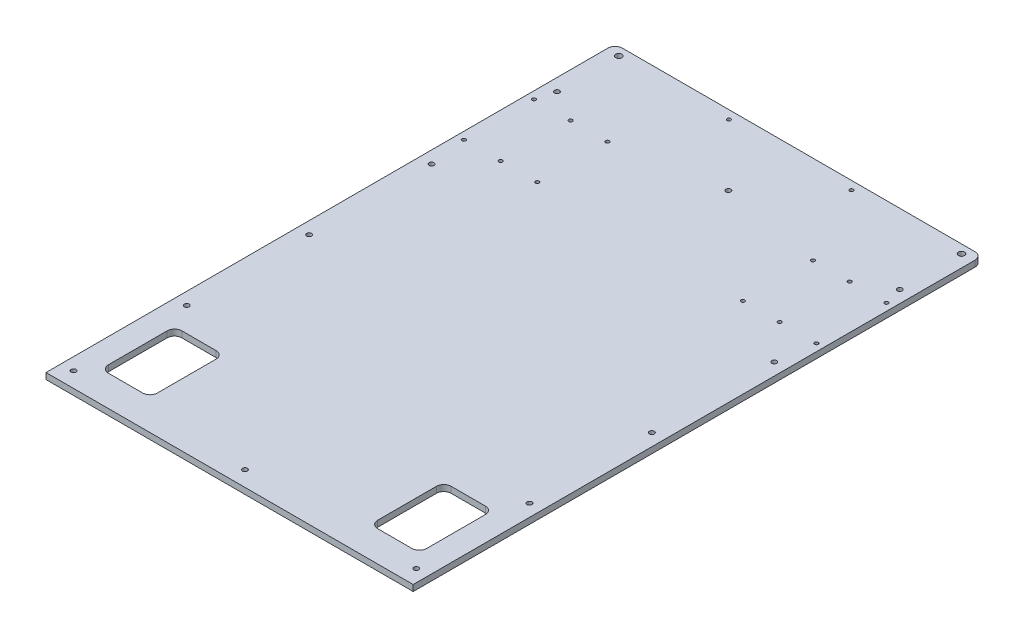
SolidWorks part; units mm, degrees
ref_plane "Front Plane" through (0, 0, 0) normal (0, 0, 1) x (1, 0, 0)
ref_plane "Top Plane" through (0, 0, 0) normal (0, 1, 0) x (1, 0, 0)
ref_plane "Right Plane" through (0, 0, 0) normal (1, 0, 0) x (0, 0, -1)
sketch "Sketch1" plane through (0, 0, 0) normal (0, 1, 0) x (1, 0, 0)
  line L0 (0, -210) -> (0, 210) construction
  line L1 (-150, -210) -> (150, -210)
  line L2 (-150, -210) -> (-150, 210)
  line L3 (-150, 210) -> (150, 210) construction
  line L4 (150, -210) -> (150, 210)
  line L5 (-150, 0) -> (150, 0) construction
  line L6 (-250, 154.9706) -> (0, 404.9706) construction
  line L7 (0, 404.9706) -> (250, 154.9706) construction
  line L8 (-130, -185) -> (-90, -185)
  line L9 (-130, -185) -> (-130, -125)
  line L10 (-130, -125) -> (-90, -125)
  line L11 (-90, -185) -> (-90, -125)
  line L12 (-130, -185) -> (-90, -125) construction
  line L13 (-130, -125) -> (-90, -185) construction
  line L14 (-250, 260) -> (250, 260) construction
  line L15 (-250, 260) -> (-250, -240) construction
  line L16 (-250, -240) -> (250, -240) construction
  line L17 (250, 260) -> (250, -240) construction
  line L18 (-188, 200) -> (-140, 200) construction
  line L19 (-165, 186) -> (-155, 186) construction
  line L20 (-165, 186) -> (-165, 122) construction
  line L21 (-165, 122) -> (-155, 122) construction
  line L22 (-155, 186) -> (-155, 122) construction
  line L23 (-140, 200) -> (-140, 248) construction
  line L24 (-140, 210) -> (-140, -210) construction
  line L25 (-150, -197.5) -> (150, -197.5) construction
  line L26 (-130, -155) -> (-90, -155) construction
  line L27 (-110, -185) -> (-110, -125) construction
  line L28 (-140, 248) -> (150, 248) construction
  line L30 (0, 182.625) -> (-150, 182.625) construction
  line L31 (130, -185) -> (90, -185)
  line L32 (130, -185) -> (130, -125)
  line L33 (130, -125) -> (90, -125)
  line L34 (90, -185) -> (90, -125)
  line L35 (-200, -205) -> (-200, 200) construction
  line L36 (-155, 154) -> (0, 154) construction
  line L37 (-150, 190) -> (0, 190) construction
  line L38 (-150, 118) -> (0, 118) construction
  line L39 (-150, 210) -> (-150, 255)
  line L40 (-150, 255) -> (150, 255)
  line L41 (150, 255) -> (150, 210)
  circle A0 centre (-140, 248) radius 12 construction
  circle A1 centre (-188, 200) radius 12 construction
  circle A2 centre (-188, -205) radius 12 construction
  circle A3 centre (0, -197.5) radius 2
  circle A4 centre (-140, -197.5) radius 2
  circle A9 centre (-140, 197.5) radius 2
  circle A10 centre (0, 197.5) radius 2
  circle A15 centre (-140, -5) radius 2
  circle A16 centre (-140, 95) radius 2
  circle A18 centre (0, 197.5) radius 2
  circle A20 centre (140, 197.5) radius 2
  circle A30 centre (140, -197.5) radius 2
  circle A31 centre (-114, 182.625) radius 1.5
  circle A32 centre (-144, 182.625) radius 1.5
  circle A33 centre (-84, 182.625) radius 1.5
  circle A34 centre (-84, 125.375) radius 1.5
  circle A35 centre (-114, 125.375) radius 1.5
  circle A36 centre (-144, 125.375) radius 1.5
  circle A37 centre (-140, -105) radius 2
  circle A38 centre (-140, 248) radius 2.5
  circle A39 centre (-50, 248) radius 1.5
  circle A40 centre (140, -105) radius 2
  circle A41 centre (140, -197.5) radius 2
  circle A42 centre (140, 95) radius 2
  circle A43 centre (140, -5) radius 2
  circle A44 centre (144, 125.375) radius 1.5
  circle A45 centre (114, 125.375) radius 1.5
  circle A46 centre (84, 125.375) radius 1.5
  circle A47 centre (84, 182.625) radius 1.5
  circle A48 centre (144, 182.625) radius 1.5
  circle A49 centre (114, 182.625) radius 1.5
  circle A50 centre (140, 197.5) radius 2
  circle A51 centre (50, 248) radius 1.5
  circle A52 centre (140, 248) radius 2.5
  point P0 (0, 0)
  point P8 (-110, -155)
  point P17 (0, -240)
  point P118 (150, 248)
  dimension "D15" = 24
  dimension "D16" = 10
  dimension "D22" = 80
  dimension "D23" = 5
  dimension "D24" = 3
  dimension "D25" = 4
  dimension "D27" = 36
  dimension "D28" = 30
  dimension "D29" = 200
  dimension "D30" = 90
  dimension "D33" = 100
  dimension "D34" = 30
  dimension "D35" = 36
  dimension "D37" = 3
  dimension "D38" = 57.25
  dimension "D20" = 4
  dimension "D21" = 100
  dimension "D1" = 300
  dimension "D2" = 420
  dimension "D3" = 60
  dimension "D4" = 40
  dimension "D5" = 20
  dimension "D6" = 25
  dimension "D7" = 500
  dimension "D8" = 500
  dimension "D9" = 45
  dimension "D10" = 45
  dimension "D11" = 50
  dimension "D12" = 64
  dimension "D13" = 10
  dimension "D14" = 5
  dimension "D17" = 5
  dimension "D18" = 10
  dimension "D19" = 12.5
  dimension "D26" = 20
  dimension "D36" = 36
  dimension "D39" = 45
  dimension "D40" = 23
extrude "Boss-Extrude1" add sketch "Sketch1" along normal blind 5 contours L41 L40 L39 L2 L1 L4 A51 A48 A43 A40 A39 A38 A37 A35 A30 A20 A16 A15 A9 A4 A3 L11 L8 L9 L10 L31 L34 L33 L32 A10 A31
fillet "Fillet1" radius 6 10 edges at (-130, 2.5, 125) (150, 2.5, -255) (-150, 2.5, -255) (130, 2.5, 185) (130, 2.5, 125) (90, 2.5, 125) (90, 2.5, 185) (-130, 2.5, 185) (-90, 2.5, 185) (-90, 2.5, 125)
